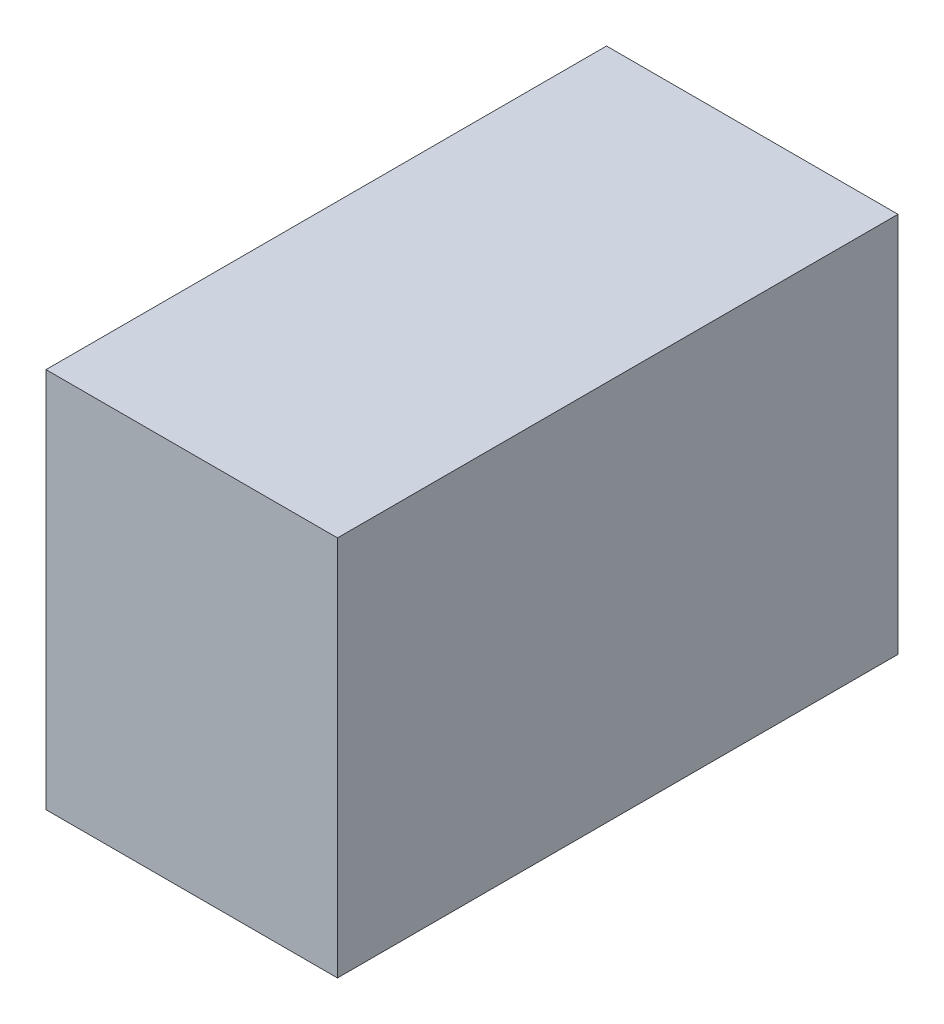
SolidWorks part; units mm, degrees
ref_plane "前视基准面" through (0, 0, 0) normal (0, 0, 1) x (1, 0, 0)
ref_plane "上视基准面" through (0, 0, 0) normal (0, 1, 0) x (1, 0, 0)
ref_plane "右视基准面" through (0, 0, 0) normal (1, 0, 0) x (0, 0, -1)
sketch "草图1" plane through (0, 0, 0) normal (0, 0, 1) x (1, 0, 0)
  line L1 (-65, 85) -> (65, 85)
  line L2 (-65, 85) -> (-65, -85)
  line L3 (-65, -85) -> (65, -85)
  line L4 (65, 85) -> (65, -85)
  line L5 (-65, 85) -> (65, -85) construction
  line L6 (-65, -85) -> (65, 85) construction
  point P0 (0, 0)
  dimension "D1" = 130
  dimension "D2" = 170
extrude "凸台-拉伸1" add sketch "草图1" along normal blind 250
